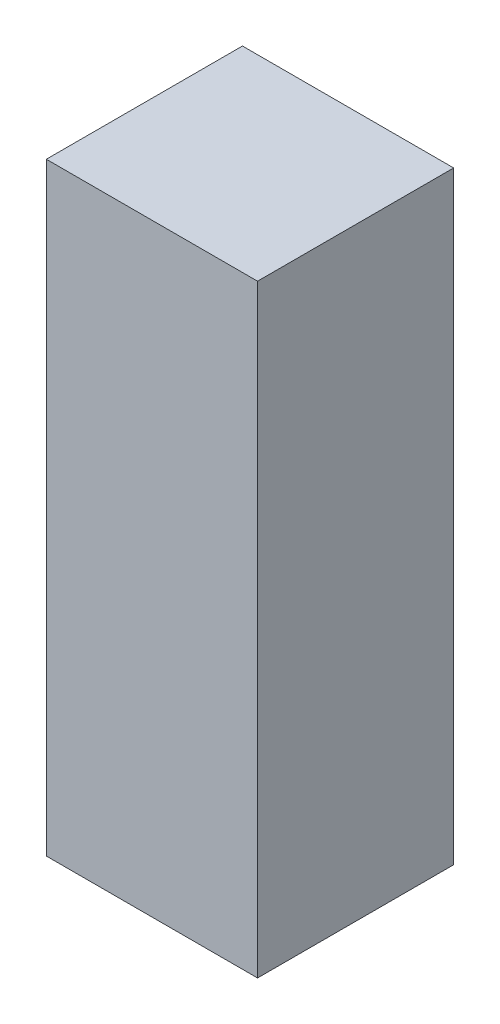
SolidWorks part; units mm, degrees
ref_plane "Front Plane" through (0, 0, 0) normal (0, 0, 1) x (1, 0, 0)
ref_plane "Top Plane" through (0, 0, 0) normal (0, 1, 0) x (1, 0, 0)
ref_plane "Right Plane" through (0, 0, 0) normal (1, 0, 0) x (0, 0, -1)
other "Configuration Table"
sketch "Sketch1" plane through (0, 0, 0) normal (0, 0, 1) x (1, 0, 0)
  line L1 (24, 160) -> (38, 160)
  line L2 (24, 160) -> (24, 200)
  line L3 (24, 200) -> (38, 200)
  line L4 (38, 160) -> (38, 200)
extrude "OVEN_pano_kapagi_mentese_1_1" add sketch "Sketch1" along normal blind 13 from offset 20 separate body
